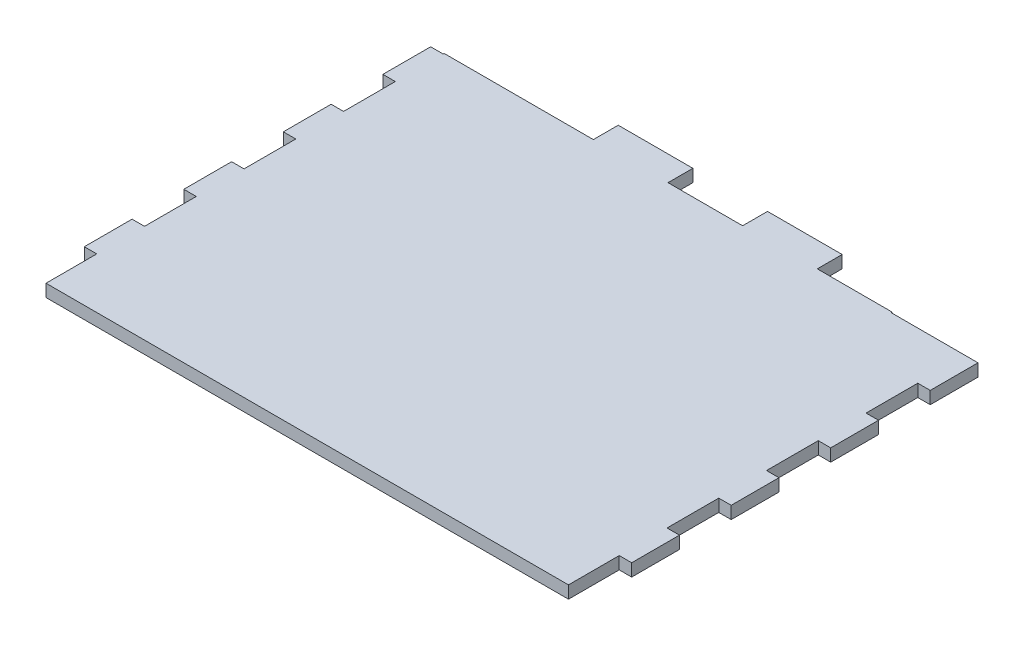
SolidWorks part; units mm, degrees
ref_plane "Front Plane" through (0, 0, 0) normal (0, 0, 1) x (1, 0, 0)
ref_plane "Top Plane" through (0, 0, 0) normal (0, 1, 0) x (1, 0, 0)
ref_plane "Right Plane" through (0, 0, 0) normal (1, 0, 0) x (0, 0, -1)
sketch "Sketch1" plane through (0, 0, 0) normal (0, 1, 0) x (1, 0, 0)
  line L1 (-66.675, -50.8) -> (66.675, -50.8)
  line L2 (-66.675, -50.8) -> (-66.675, 50.8)
  line L3 (-66.675, 50.8) -> (66.675, 50.8)
  line L4 (66.675, -50.8) -> (66.675, 50.8)
  line L5 (-66.675, -50.8) -> (66.675, 50.8) construction
  line L6 (-66.675, 50.8) -> (66.675, -50.8) construction
  point P0 (0, 0)
  dimension "D1" = 133.35
  dimension "D2" = 101.6
extrude "Boss-Extrude1" add sketch "Sketch1" along normal blind 3.175
sketch "Sketch2" plane through (0, 0, 0) normal (0, -1, 0) x (-1, 0, 0)
  line L0 (66.675, 50.8) -> (66.675, -50.8) construction
  line L1 (66.675, -37.846) -> (69.85, -37.846)
  line L2 (66.675, -37.846) -> (66.675, -25.654)
  line L3 (66.675, -25.654) -> (69.85, -25.654)
  line L4 (69.85, -37.846) -> (69.85, -25.654)
  line L6 (66.675, -12.446) -> (69.85, -12.446)
  line L7 (66.675, -12.446) -> (66.675, -0.254)
  line L8 (66.675, -0.254) -> (69.85, -0.254)
  line L9 (69.85, -12.446) -> (69.85, -0.254)
  line L10 (66.675, 12.954) -> (69.85, 12.954)
  line L11 (66.675, 12.954) -> (66.675, 25.146)
  line L12 (66.675, 25.146) -> (69.85, 25.146)
  line L13 (69.85, 12.954) -> (69.85, 25.146)
  line L14 (66.675, 38.354) -> (69.85, 38.354)
  line L15 (66.675, 38.354) -> (66.675, 50.546)
  line L16 (66.675, 50.546) -> (69.85, 50.546)
  line L17 (69.85, 38.354) -> (69.85, 50.546)
  line L18 (0, 0) -> (0, -50.8) construction
  line L19 (66.675, -50.8) -> (-66.675, -50.8) construction
  line L20 (-69.85, 38.354) -> (-69.85, 50.546)
  line L21 (-66.675, 50.546) -> (-69.85, 50.546)
  line L22 (-66.675, 38.354) -> (-66.675, 50.546)
  line L23 (-66.675, 38.354) -> (-69.85, 38.354)
  line L24 (-69.85, 12.954) -> (-69.85, 25.146)
  line L25 (-66.675, 25.146) -> (-69.85, 25.146)
  line L26 (-66.675, 12.954) -> (-66.675, 25.146)
  line L27 (-66.675, 12.954) -> (-69.85, 12.954)
  line L28 (-69.85, -12.446) -> (-69.85, -0.254)
  line L29 (-66.675, -0.254) -> (-69.85, -0.254)
  line L30 (-66.675, -12.446) -> (-66.675, -0.254)
  line L31 (-66.675, -12.446) -> (-69.85, -12.446)
  line L32 (-69.85, -37.846) -> (-69.85, -25.654)
  line L33 (-66.675, -25.654) -> (-69.85, -25.654)
  line L34 (-66.675, -37.846) -> (-66.675, -25.654)
  line L35 (-66.675, -37.846) -> (-69.85, -37.846)
  line L36 (28.575, 57.15) -> (9.525, 57.15)
  line L37 (66.675, 50.8) -> (47.625, 50.8)
  line L38 (66.675, 50.8) -> (66.675, 57.15)
  line L39 (66.675, 57.15) -> (47.625, 57.15)
  line L40 (47.625, 50.8) -> (47.625, 57.15)
  line L41 (9.525, 50.8) -> (9.525, 57.15)
  line L42 (28.575, 50.8) -> (9.525, 50.8)
  line L43 (28.575, 50.8) -> (28.575, 57.15)
  line L44 (-9.525, 57.15) -> (-28.575, 57.15)
  line L45 (-28.575, 50.8) -> (-28.575, 57.15)
  line L46 (-9.525, 50.8) -> (-28.575, 50.8)
  line L47 (-9.525, 50.8) -> (-9.525, 57.15)
  line L48 (-47.625, 57.15) -> (-66.675, 57.15)
  line L49 (-66.675, 50.8) -> (-66.675, 57.15)
  line L50 (-47.625, 50.8) -> (-66.675, 50.8)
  line L51 (-47.625, 50.8) -> (-47.625, 57.15)
  point P6 (69.85, -31.75)
  point P46 (66.675, 53.975)
  dimension "D1" = 3.175
  dimension "D2" = 19.05
  dimension "D3" = 12.192
  dimension "D5" = 6.35
  dimension "D6" = 19.05
  dimension "D8" = 38.1
  dimension "D4" = 4
  dimension "D7" = 4
extrude "Boss-Extrude2" add sketch "Sketch2" against normal blind 3.175
sketch "Sketch3" plane through (0, 0, 0) normal (0, 1, 0) x (1, 0, 0)
  line L1 (-66.675, 57.15) -> (-47.625, 57.15)
  line L2 (-66.675, 57.15) -> (-66.675, 50.8)
  line L3 (-66.675, 50.8) -> (-47.625, 50.8)
  line L4 (-47.625, 57.15) -> (-47.625, 50.8)
  line L5 (47.625, 57.15) -> (66.675, 57.15)
  line L6 (47.625, 57.15) -> (47.625, 50.546)
  line L7 (47.625, 50.546) -> (66.675, 50.546)
  line L8 (66.675, 57.15) -> (66.675, 50.546)
extrude "Cut-Extrude1" cut sketch "Sketch3" along normal through all
